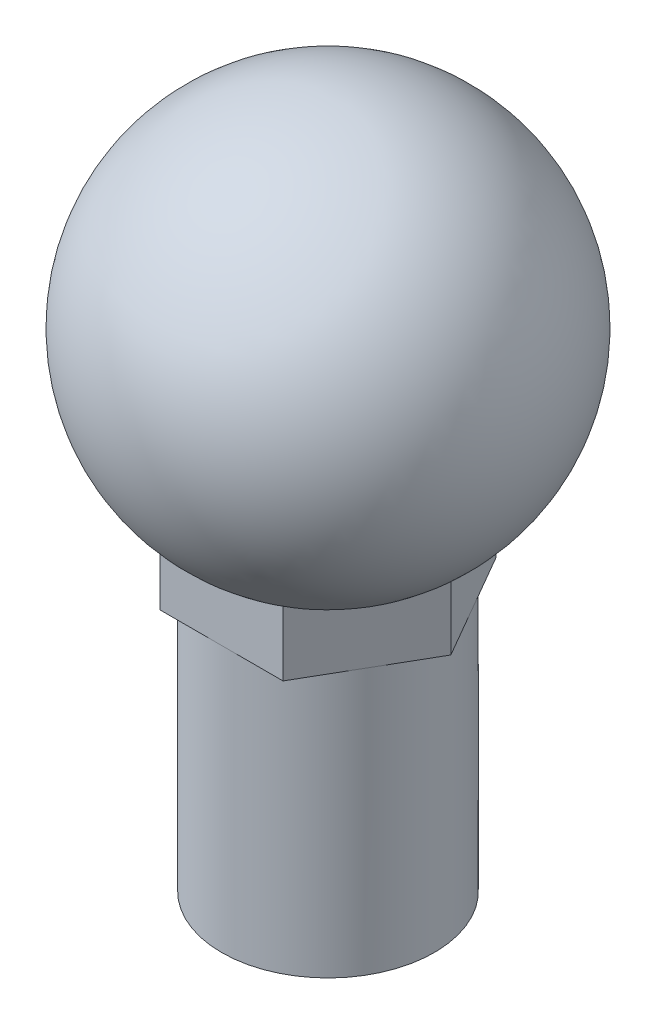
SolidWorks part; units mm, degrees
ref_plane "Front Plane" through (0, 0, 0) normal (0, 0, 1) x (1, 0, 0)
ref_plane "Top Plane" through (0, 0, 0) normal (0, 1, 0) x (1, 0, 0)
ref_plane "Right Plane" through (0, 0, 0) normal (1, 0, 0) x (0, 0, -1)
sketch "Sketch1" plane through (0, 0, 0) normal (0, 1, 0) x (1, 0, 0)
  circle A0 centre (0, 0) radius 4
  dimension "D1" = 8
extrude "Boss-Extrude1" add sketch "Sketch1" along normal blind 12
sketch "Sketch2" plane through (0, 0, 0) normal (0, 0, 1) x (1, 0, 0)
  line L0 (0, 25.8443) -> (0, 10.8443)
  arc A0 (0, 10.8443) -> (0, 25.8443) centre (0, 18.3443) ccw
  dimension "D1" = 15
revolve "Revolve1" add sketch "Sketch2" angle 360 about L0
ref_plane "Plane1" through (0, 13, 0) normal (0, -1, 0) x (-1, 0, 0)
sketch "Sketch4" plane through (0, 13, 0) normal (0, -1, 0) x (-1, 0, 0)
  line L1 (2.3094, 4) -> (-2.3094, 4)
  line L2 (-2.3094, 4) -> (-4.6188, 0)
  line L3 (-4.6188, 0) -> (-2.3094, -4)
  line L4 (-2.3094, -4) -> (2.3094, -4)
  line L5 (2.3094, -4) -> (4.6188, 0)
  line L6 (4.6188, 0) -> (2.3094, 4)
  circle A0 centre (0, 0) radius 4 construction
  dimension "D1" = 8
extrude "Boss-Extrude3" add sketch "Sketch4" along normal blind 3
